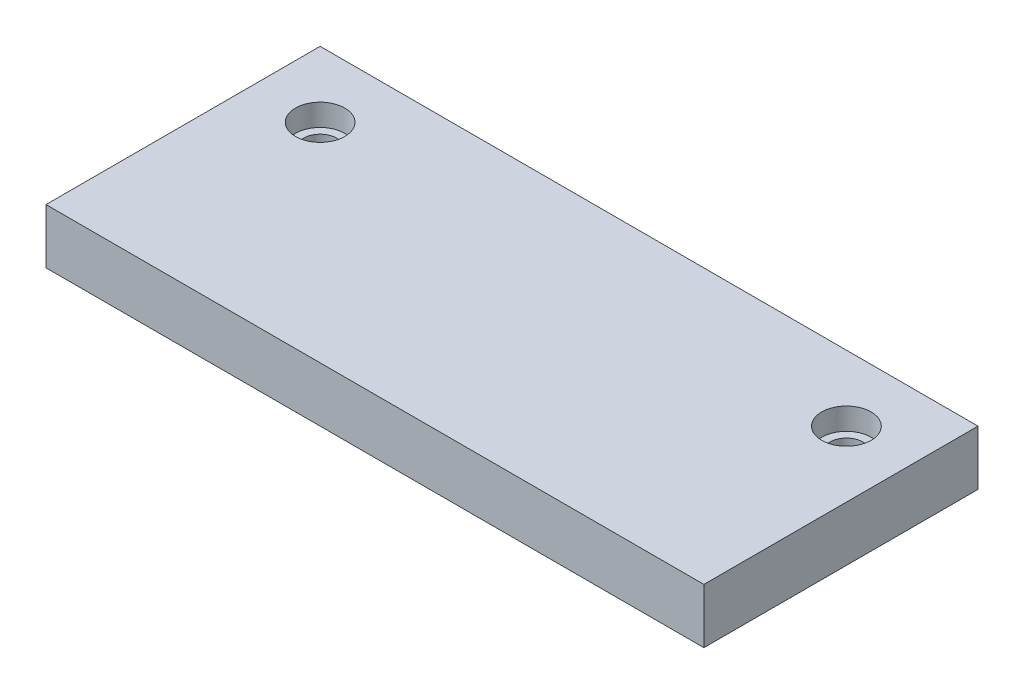
SolidWorks part; units mm, degrees
ref_plane "Front Plane" through (0, 0, 0) normal (0, 0, 1) x (1, 0, 0)
ref_plane "Top Plane" through (0, 0, 0) normal (0, 1, 0) x (1, 0, 0)
ref_plane "Right Plane" through (0, 0, 0) normal (1, 0, 0) x (0, 0, -1)
sketch "Sketch1" plane through (0, 0, 0) normal (0, 1, 0) x (1, 0, 0)
  line L0 (54, 19) -> (54, 25) construction
  line L1 (0, 0) -> (60, 0)
  line L2 (0, 0) -> (0, 25)
  line L3 (0, 25) -> (60, 25)
  line L4 (60, 0) -> (60, 25)
  line L5 (6, 19) -> (6, 25) construction
  line L6 (6, 19) -> (0, 19) construction
  line L7 (54, 19) -> (60, 19) construction
  circle A0 centre (6, 19) radius 1.5
  circle A1 centre (54, 19) radius 1.5
  point P9 (3, 11.9044)
  dimension "D3" = 3
  dimension "D1" = 6
  dimension "D2" = 6
  dimension "D4" = 25
  dimension "D5" = 60
extrude "Boss-Extrude1" add sketch "Sketch1" along normal blind 5 contours L2 L3 L4 L1 | A0 | A1
sketch "Sketch2" plane through (0, 5, 0) normal (0, 1, 0) x (1, 0, 0)
  circle A0 centre (6, 19) radius 2.25
  circle A1 centre (54, 19) radius 2.25
  dimension "D1" = 4.5
extrude "Cut-Extrude1" cut sketch "Sketch2" against normal blind 2
